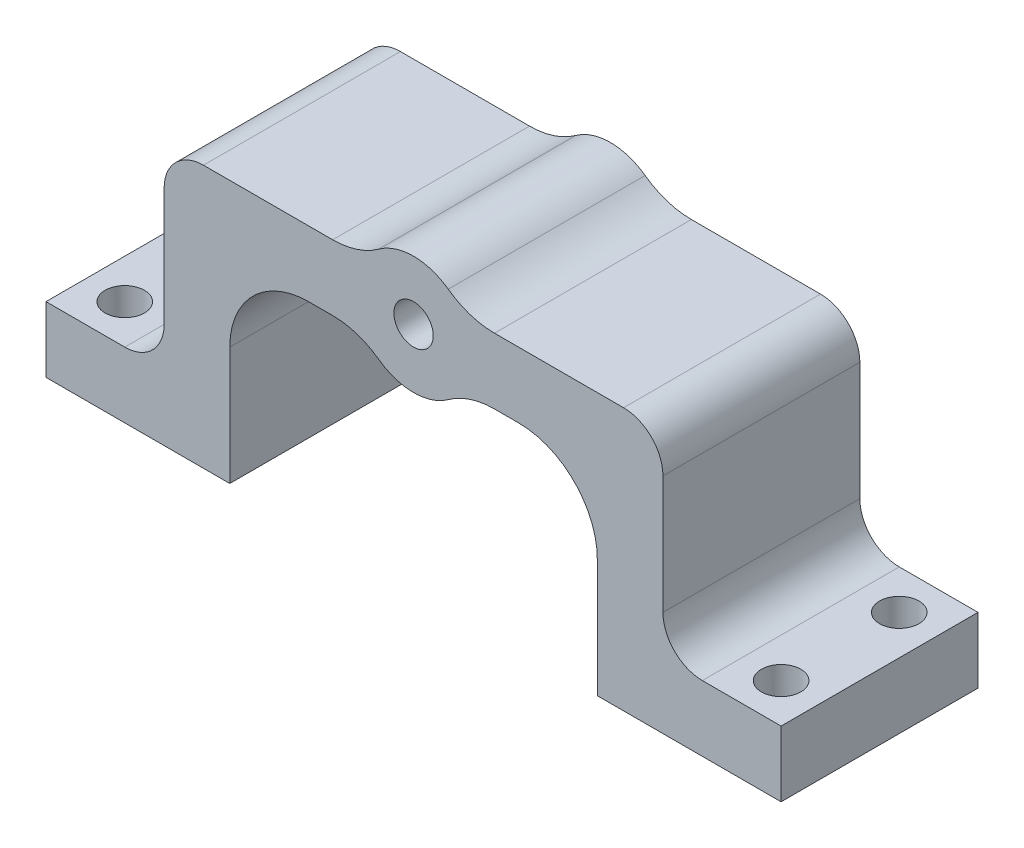
SolidWorks part; units mm, degrees
material "6061 合金"
ref_plane "前视基准面" through (0, 0, 0) normal (0, 0, 1) x (1, 0, 0)
ref_plane "上视基准面" through (0, 0, 0) normal (0, 1, 0) x (1, 0, 0)
ref_plane "右视基准面" through (0, 0, 0) normal (1, 0, 0) x (0, 0, -1)
sketch "草图1" plane through (0, 0, 0) normal (0, 0, 1) x (1, 0, 0)
  line L0 (-28, 0) -> (-14, 0)
  line L1 (28, 0) -> (28, 5)
  line L2 (28, 5) -> (19, 5)
  line L3 (19, 5) -> (19, 20)
  line L4 (19, 20) -> (-19, 20)
  line L5 (-19, 5) -> (-19, 20)
  line L6 (0, 0) -> (0, 26.8404) construction
  line L7 (-28, 5) -> (-19, 5)
  line L8 (-28, 0) -> (-28, 5)
  line L9 (-14, 0) -> (-14, 15)
  line L10 (-14, 15) -> (14, 15)
  line L11 (14, 0) -> (14, 15)
  line L12 (10.7809, 0) -> (28, 0)
  point P9 (0, 20)
  point P17 (0, 15)
  dimension "D1" = 56
  dimension "D2" = 20
  dimension "D3" = 5
  dimension "D4" = 38
  dimension "D5" = 28
  dimension "D6" = 5
  dimension "D7" = 0
extrude "凸台-拉伸1" add sketch "草图1" along normal mid plane 15 contours L10 L6 L4 L5 L7 L8 L0 L9 | L6 L10 L11 L12 L1 L2 L3 L4
fillet "圆角1" radius 3 4 edges at (19, 5, 0) (-19, 5, 0) (19, 20, 0) (-19, 20, 0)
fillet "圆角3" radius 6 2 edges at (14, 15, 0) (-14, 15, 0)
sketch "草图2" plane through (0, 5, 0) normal (0, 1, 0) x (1, 0, 0)
  line L1 (0, 0) -> (20.1105, 0) construction
  circle A0 centre (25, -4.5) radius 1.5
  circle A1 centre (25, 4.5) radius 1.5
  dimension "D2" = 3
  dimension "D3" = 25
  dimension "D5" = 9
extrude "切除-拉伸1" cut sketch "草图2" against normal blind 10
sketch "草图5" plane through (0, 0, 7.5) normal (0, 0, 1) x (1, 0, 0)
  line L0 (16, 20) -> (-16, 20) construction
  circle A0 centre (0, 17.5) radius 4.5
  dimension "D1" = 9
  dimension "D2" = 0
  dimension "D3" = 2.5
extrude "凸台-拉伸2" add sketch "草图5" against normal blind 15
sketch "草图4" plane through (0, 0, 7.5) normal (0, 0, 1) x (1, 0, 0)
  line L0 (19, 20) -> (-19, 20) construction
  circle A0 centre (0, 17.5) radius 1.5
  dimension "D1" = 3
  dimension "D2" = 0
  dimension "D3" = 2.5
extrude "切除-拉伸3" cut sketch "草图4" against normal through all
mirror "镜向2" about plane through (0, 0, 0) normal (1, 0, 0) of "切除-拉伸1"
fillet "圆角2" radius 6 4 edges at (-3.7417, 15, 0) (3.7417, 15, 0) (3.7417, 20, 0) (-3.7417, 20, 0)
